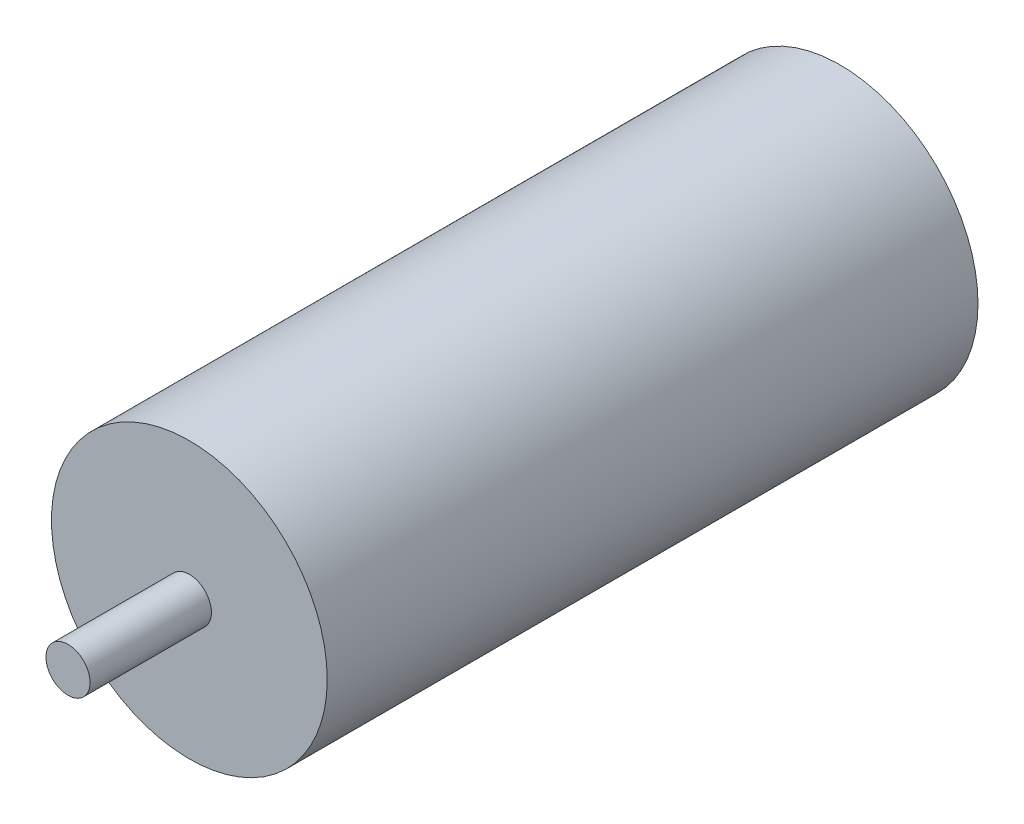
SolidWorks part; units mm, degrees
ref_plane "Front Plane" through (0, 0, 0) normal (0, 0, 1) x (1, 0, 0)
ref_plane "Top Plane" through (0, 0, 0) normal (0, 1, 0) x (1, 0, 0)
ref_plane "Right Plane" through (0, 0, 0) normal (1, 0, 0) x (0, 0, -1)
sketch "Sketch1" plane through (0, 0, 0) normal (0, 0, 1) x (1, 0, 0)
  circle A0 centre (0, 0) radius 2
  dimension "D1" = 4
extrude "Boss-Extrude1" add sketch "Sketch1" along normal blind 11
sketch "Sketch2" plane through (0, 0, 0) normal (0, 0, -1) x (-1, 0, 0)
  circle A0 centre (0, 0) radius 12.5
  dimension "D1" = 25
extrude "Boss-Extrude2" add sketch "Sketch2" along normal blind 59
